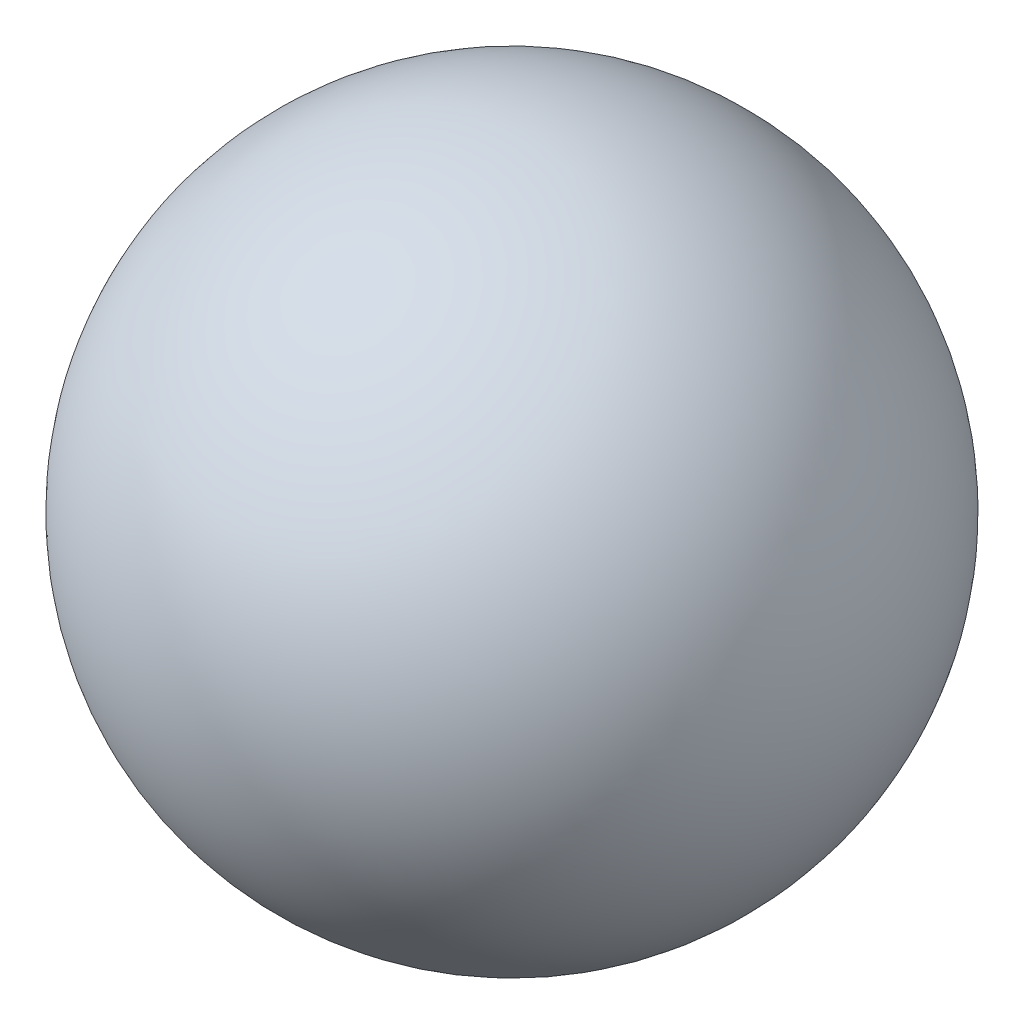
SolidWorks part; units mm, degrees
ref_plane "Front Plane" through (0, 0, 0) normal (0, 0, 1) x (1, 0, 0)
ref_plane "Top Plane" through (0, 0, 0) normal (0, 1, 0) x (1, 0, 0)
ref_plane "Right Plane" through (0, 0, 0) normal (1, 0, 0) x (0, 0, -1)
sketch "Sketch1" plane through (0, 0, 0) normal (0, 0, 1) x (1, 0, 0)
  line L0 (-12, 0) -> (12, 0)
  arc A0 (12, 0) -> (-12, 0) centre (0, 0) cw
  dimension "D1" = 24
revolve "Revolve1" add sketch "Sketch1" angle 360 about L0
scale "Scale1" scale about centroid uniform scaling yes scale factor 0.19304
